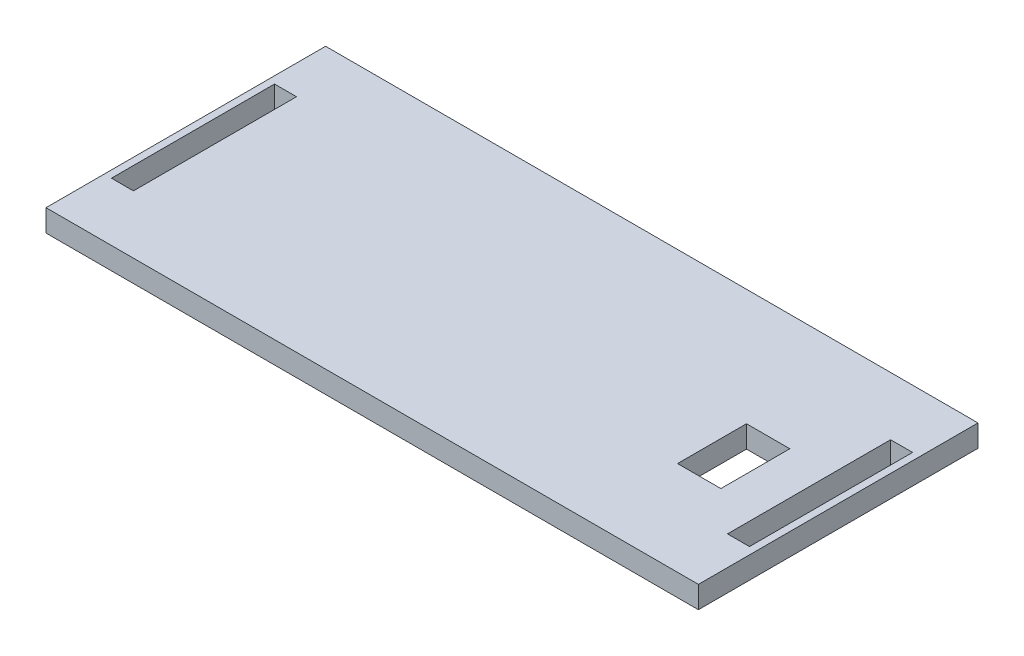
SolidWorks part; units mm, degrees
ref_plane "Front Plane" through (0, 0, 0) normal (0, 0, 1) x (1, 0, 0)
ref_plane "Top Plane" through (0, 0, 0) normal (0, 1, 0) x (1, 0, 0)
ref_plane "Right Plane" through (0, 0, 0) normal (1, 0, 0) x (0, 0, -1)
sketch "Sketch1" plane through (0, 0, 0) normal (0, 1, 0) x (1, 0, 0)
  line L1 (0, 0) -> (177.8, 0)
  line L2 (0, 0) -> (0, -76.2)
  line L3 (0, -76.2) -> (177.8, -76.2)
  line L4 (177.8, 0) -> (177.8, -76.2)
  line L5 (1.9548, -15.875) -> (7.9492, -15.875)
  line L6 (1.9548, -15.875) -> (1.9548, -60.325)
  line L7 (1.9548, -60.325) -> (7.9492, -60.325)
  line L8 (7.9492, -15.875) -> (7.9492, -60.325)
  line L9 (175.8452, -15.875) -> (169.8508, -15.875)
  line L10 (175.8452, -15.875) -> (175.8452, -60.325)
  line L11 (175.8452, -60.325) -> (169.8508, -60.325)
  line L12 (169.8508, -15.875) -> (169.8508, -60.325)
  line L13 (158.2557, -31.7373) -> (146.4447, -31.7373)
  line L14 (158.2557, -31.7373) -> (158.2557, -50.5333)
  line L15 (158.2557, -50.5333) -> (146.4447, -50.5333)
  line L16 (146.4447, -31.7373) -> (146.4447, -50.5333)
  point P9 (1.9548, -38.1)
  point P10 (0, -38.1)
  point P15 (175.8452, -38.1)
  point P16 (177.8, -38.1)
  point P22 (169.8508, -38.1)
  dimension "D1" = 177.8
  dimension "D2" = 76.2
  dimension "D3" = 44.45
  dimension "D4" = 5.9944
  dimension "D5" = 1.9548
  dimension "D6" = 5.9944
  dimension "D7" = 44.45
  dimension "D8" = 1.9548
  dimension "D9" = 11.811
  dimension "D10" = 18.796
  dimension "D11" = 11.5951
  dimension "D12" = 25.6667
extrude "Boss-Extrude1" add sketch "Sketch1" along normal blind 5.9944
